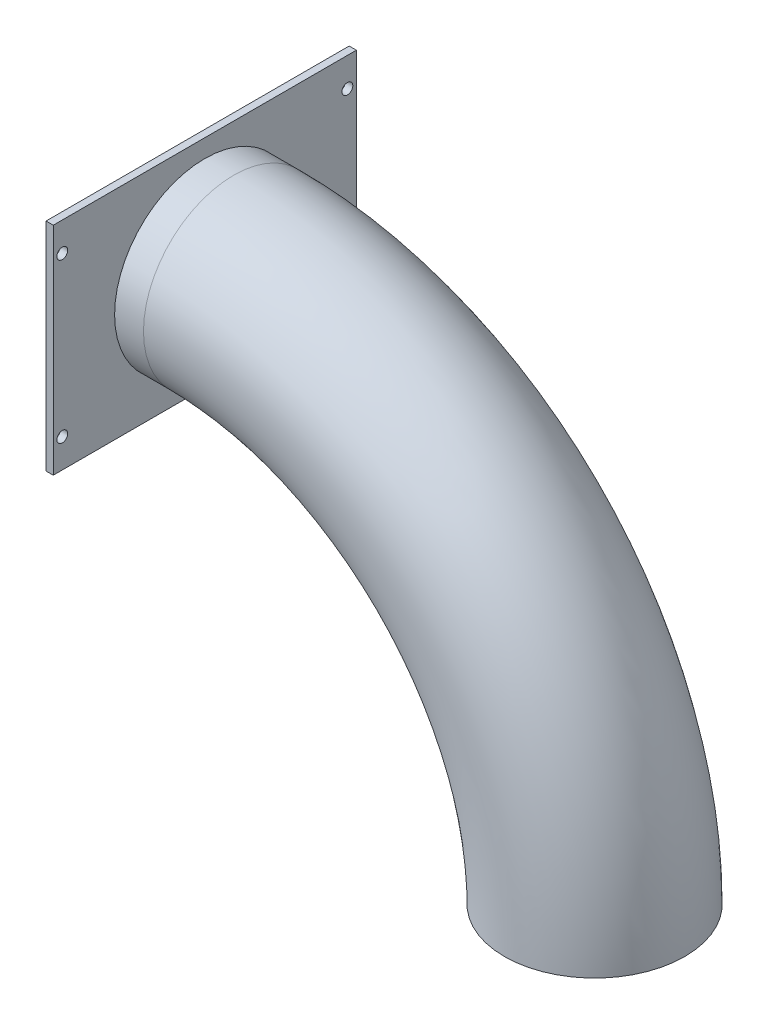
SolidWorks part; units mm, degrees
ref_plane "Ön Düzlem" through (0, 0, 0) normal (0, 0, 1) x (1, 0, 0)
ref_plane "Üst Düzlem" through (0, 0, 0) normal (0, 1, 0) x (1, 0, 0)
ref_plane "Sağ Düzlem" through (0, 0, 0) normal (1, 0, 0) x (0, 0, -1)
sketch "Çizim1" plane through (0, 0, 0) normal (0, 0, 1) x (1, 0, 0)
  line L0 (-100, 100) -> (-108, 100)
  arc A0 (0, 0) -> (-100, 100) centre (-100, 0) ccw
  dimension "D1" = 100
  dimension "D2" = 8
sketch "Çizim2" plane through (0, 0, 0) normal (0, 1, 0) x (1, 0, 0)
  circle A0 centre (0, 0) radius 25
  dimension "D1" = 50
sweep "Süpür1" add profiles "Çizim2" path "Çizim1"
sketch "Çizim3" plane through (0, 0, 0) normal (0, 0, 1) x (1, 0, 0)
  line L0 (-100, 100) -> (-108, 100) construction
  line L1 (-100, 100) -> (-108, 100)
  arc A0 (0, 0) -> (-100, 100) centre (-100, 0) ccw construction
  arc A1 (0, 0) -> (-100, 100) centre (-100, 0) ccw
sketch "Çizim4" plane through (0, 0, 0) normal (0, 1, 0) x (1, 0, 0)
  circle A0 centre (0, 0) radius 24
  dimension "D1" = 48
sweep "Kes-Süpür1" cut profiles "Çizim4" path "Çizim3"
sketch "Çizim5" plane through (-108, 0, 0) normal (-1, 0, 0) x (0, 0, 1)
  line L1 (42, 130) -> (-42, 130)
  line L2 (42, 130) -> (42, 70)
  line L3 (42, 70) -> (-42, 70)
  line L4 (-42, 130) -> (-42, 70)
  circle A0 centre (0, 100) radius 24 construction
  circle A1 centre (0, 100) radius 24
  circle A2 centre (-39.5, 122) radius 1.5
  circle A3 centre (39.5, 122) radius 1.5
  circle A4 centre (39.5, 78) radius 1.5
  circle A5 centre (-39.5, 78) radius 1.5
  dimension "D3" = 30
  dimension "D6" = 3
  dimension "D1" = 84
  dimension "D2" = 60
  dimension "D4" = 42
  dimension "D5" = 39.5
  dimension "D7" = 22
  dimension "D8" = 2
  dimension "D9" = 2
extrude "Yükseklik-Ekstrüzyon1" add sketch "Çizim5" along normal blind 2
